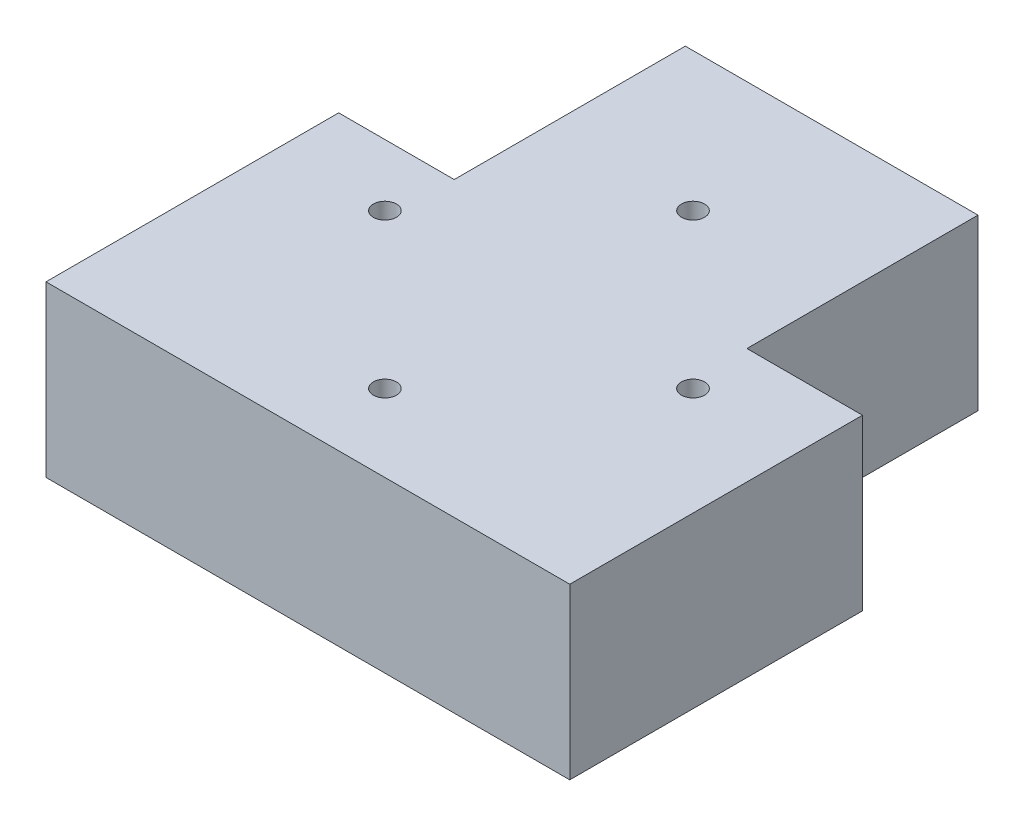
SolidWorks part; units mm, degrees
ref_plane "Alzado" through (0, 0, 0) normal (0, 0, 1) x (1, 0, 0)
ref_plane "Planta" through (0, 0, 0) normal (0, 1, 0) x (1, 0, 0)
ref_plane "Vista lateral" through (0, 0, 0) normal (1, 0, 0) x (0, 0, -1)
sketch "Croquis3" plane through (0, 0, 0) normal (0, 1, 0) x (1, 0, 0)
  circle A0 centre (0, 0) radius 11
  arc A1 (-42.801, 4.1321) -> (-38.4151, 2.54) centre (-35.0691, 18.5951) ccw
  arc A2 (-38.4151, 2.54) -> (-38.4968, 0.4081) centre (0, 0) ccw
  arc A3 (-38.4968, 0.4081) -> (-42.9917, -0.8436) centre (-36.3896, -15.856) ccw
  arc A4 (-42.9917, -0.8436) -> (-42.9302, -2.4499) centre (0, 0) ccw
  arc A5 (-42.9302, -2.4499) -> (-38.3526, -3.3538) centre (-37.4966, 13.0239) ccw
  arc A6 (-38.3526, -3.3538) -> (-38.108, -5.4732) centre (0, 0) ccw
  arc A7 (-38.108, -5.4732) -> (-42.3591, -7.3964) centre (-33.5427, -21.225) ccw
  arc A8 (-42.3591, -7.3964) -> (-42.0531, -8.9744) centre (0, 0) ccw
  arc A9 (-42.0531, -8.9744) -> (-37.3912, -9.169) centre (-39.0453, 7.1474) ccw
  arc A10 (-37.3912, -9.169) -> (-36.8259, -11.2263) centre (0, 0) ccw
  arc A11 (-36.8259, -11.2263) -> (-40.7336, -13.7758) centre (-29.9097, -26.0966) ccw
  arc A12 (-40.7336, -13.7758) -> (-40.1903, -15.2886) centre (0, 0) ccw
  arc A13 (-40.1903, -15.2886) -> (-35.5534, -14.7692) centre (-39.6787, 1.1034) ccw
  arc A14 (-35.5534, -14.7692) -> (-34.6806, -16.7161) centre (0, 0) ccw
  arc A15 (-34.6806, -16.7161) -> (-38.1534, -19.8323) centre (-25.5755, -30.3564) ccw
  arc A16 (-38.1534, -19.8323) -> (-37.3855, -21.2444) centre (0, 0) ccw
  arc A17 (-37.3855, -21.2444) -> (-32.8822, -20.0234) centre (-39.3821, -4.9664) ccw
  arc A18 (-32.8822, -20.0234) -> (-31.7225, -21.8142) centre (0, 0) ccw
  arc A19 (-31.7225, -21.8142) -> (-34.6789, -25.4239) centre (-20.6419, -33.9047) ccw
  arc A20 (-34.6789, -25.4239) -> (-33.7044, -26.7023) centre (0, 0) ccw
  arc A21 (-33.7044, -26.7023) -> (-29.4403, -24.8081) centre (-38.1625, -10.9199) ccw
  arc A22 (-29.4403, -24.8081) -> (-28.0208, -26.4009) centre (0, 0) ccw
  arc A23 (-28.0208, -26.4009) -> (-30.3915, -30.4197) centre (-15.2244, -36.6583) ccw
  arc A24 (-30.3915, -30.4197) -> (-29.2333, -31.5343) centre (0, 0) ccw
  arc A25 (-29.2333, -31.5343) -> (-25.3083, -29.0114) centre (-36.0483, -16.6174) ccw
  arc A26 (-25.3083, -29.0114) -> (-23.6623, -30.3689) centre (0, 0) ccw
  arc A27 (-23.6623, -30.3689) -> (-25.3918, -34.7024) centre (-9.4501, -38.5527) ccw
  arc A28 (-25.3918, -34.7024) -> (-24.077, -35.6272) centre (0, 0) ccw
  arc A29 (-24.077, -35.6272) -> (-20.5831, -32.5347) centre (-33.0892, -21.9254) ccw
  arc A30 (-20.5831, -32.5347) -> (-18.7492, -33.625) centre (0, 0) ccw
  arc A31 (-18.7492, -33.625) -> (-19.7969, -38.1718) centre (-3.4543, -39.5435) ccw
  arc A32 (-19.7969, -38.1718) -> (-18.3564, -38.885) centre (0, 0) ccw
  arc A33 (-18.3564, -38.885) -> (-15.3755, -35.2954) centre (-29.3545, -26.7195) ccw
  arc A34 (-15.3755, -35.2954) -> (-13.3966, -36.093) centre (0, 0) ccw
  arc A35 (-13.3966, -36.093) -> (-13.738, -40.7464) centre (2.6224, -39.6073) ccw
  arc A36 (-13.738, -40.7464) -> (-12.2055, -41.2314) centre (0, 0) ccw
  arc A37 (-12.2055, -41.2314) -> (-9.8075, -37.2288) centre (-24.9318, -30.8873) ccw
  arc A38 (-9.8075, -37.2288) -> (-7.73, -37.715) centre (0, 0) ccw
  arc A39 (-7.73, -37.715) -> (-7.3571, -42.3659) centre (8.6377, -38.7428) ccw
  arc A40 (-7.3571, -42.3659) -> (-5.7685, -42.6113) centre (0, 0) ccw
  arc A41 (-5.7685, -42.6113) -> (-4.0096, -38.2896) centre (-19.9247, -34.3311) ccw
  arc A42 (-4.0096, -38.2896) -> (-1.8823, -38.453) centre (0, 0) ccw
  arc A43 (-1.8823, -38.453) -> (-0.8037, -42.9925) centre (14.4506, -36.9703) ccw
  arc A44 (-0.8037, -42.9925) -> (0.8037, -42.9925) centre (0, 0) ccw
  arc A45 (0.8037, -42.9925) -> (1.8823, -38.453) centre (-14.4506, -36.9703) ccw
  arc A46 (1.8823, -38.453) -> (4.0096, -38.2896) centre (0, 0) ccw
  arc A47 (4.0096, -38.2896) -> (5.7685, -42.6113) centre (19.9247, -34.3311) ccw
  arc A48 (5.7685, -42.6113) -> (7.3571, -42.3659) centre (0, 0) ccw
  arc A49 (7.3571, -42.3659) -> (7.73, -37.715) centre (-8.6377, -38.7428) ccw
  arc A50 (7.73, -37.715) -> (9.8075, -37.2288) centre (0, 0) ccw
  arc A51 (9.8075, -37.2288) -> (12.2055, -41.2314) centre (24.9318, -30.8873) ccw
  arc A52 (12.2055, -41.2314) -> (13.738, -40.7464) centre (0, 0) ccw
  arc A53 (13.738, -40.7464) -> (13.3966, -36.093) centre (-2.6224, -39.6073) ccw
  arc A54 (13.3966, -36.093) -> (15.3755, -35.2954) centre (0, 0) ccw
  arc A55 (15.3755, -35.2954) -> (18.3564, -38.885) centre (29.3545, -26.7195) ccw
  arc A56 (18.3564, -38.885) -> (19.7969, -38.1718) centre (0, 0) ccw
  arc A57 (19.7969, -38.1718) -> (18.7492, -33.625) centre (3.4543, -39.5435) ccw
  arc A58 (18.7492, -33.625) -> (20.5831, -32.5347) centre (0, 0) ccw
  arc A59 (20.5831, -32.5347) -> (24.077, -35.6272) centre (33.0892, -21.9254) ccw
  arc A60 (24.077, -35.6272) -> (25.3918, -34.7024) centre (0, 0) ccw
  arc A61 (25.3918, -34.7024) -> (23.6623, -30.3689) centre (9.4501, -38.5527) ccw
  arc A62 (23.6623, -30.3689) -> (25.3083, -29.0114) centre (0, 0) ccw
  arc A63 (25.3083, -29.0114) -> (29.2333, -31.5343) centre (36.0483, -16.6174) ccw
  arc A64 (29.2333, -31.5343) -> (30.3915, -30.4197) centre (0, 0) ccw
  arc A65 (30.3915, -30.4197) -> (28.0208, -26.4009) centre (15.2244, -36.6583) ccw
  arc A66 (28.0208, -26.4009) -> (29.4403, -24.8081) centre (0, 0) ccw
  arc A67 (29.4403, -24.8081) -> (33.7044, -26.7023) centre (38.1625, -10.9199) ccw
  arc A68 (33.7044, -26.7023) -> (34.6789, -25.4239) centre (0, 0) ccw
  arc A69 (34.6789, -25.4239) -> (31.7225, -21.8142) centre (20.6419, -33.9047) ccw
  arc A70 (31.7225, -21.8142) -> (32.8822, -20.0234) centre (0, 0) ccw
  arc A71 (32.8822, -20.0234) -> (37.3855, -21.2444) centre (39.3821, -4.9664) ccw
  arc A72 (37.3855, -21.2444) -> (38.1534, -19.8323) centre (0, 0) ccw
  arc A73 (38.1534, -19.8323) -> (34.6806, -16.7161) centre (25.5755, -30.3564) ccw
  arc A74 (34.6806, -16.7161) -> (35.5534, -14.7692) centre (0, 0) ccw
  arc A75 (35.5534, -14.7692) -> (40.1903, -15.2886) centre (39.6787, 1.1034) ccw
  arc A76 (40.1903, -15.2886) -> (40.7336, -13.7758) centre (0, 0) ccw
  arc A77 (40.7336, -13.7758) -> (36.8259, -11.2263) centre (29.9097, -26.0966) ccw
  arc A78 (36.8259, -11.2263) -> (37.3912, -9.169) centre (0, 0) ccw
  arc A79 (37.3912, -9.169) -> (42.0531, -8.9744) centre (39.0453, 7.1474) ccw
  arc A80 (42.0531, -8.9744) -> (42.3591, -7.3964) centre (0, 0) ccw
  arc A81 (42.3591, -7.3964) -> (38.108, -5.4732) centre (33.5427, -21.225) ccw
  arc A82 (38.108, -5.4732) -> (38.3526, -3.3538) centre (0, 0) ccw
  arc A83 (38.3526, -3.3538) -> (42.9302, -2.4499) centre (37.4966, 13.0239) ccw
  arc A84 (42.9302, -2.4499) -> (42.9917, -0.8436) centre (0, 0) ccw
  arc A85 (42.9917, -0.8436) -> (38.4968, 0.4081) centre (36.3896, -15.856) ccw
  arc A86 (38.4968, 0.4081) -> (38.4151, 2.54) centre (0, 0) ccw
  arc A87 (38.4151, 2.54) -> (42.801, 4.1321) centre (35.0691, 18.5951) ccw
  arc A88 (42.801, 4.1321) -> (42.6167, 5.7289) centre (0, 0) ccw
  arc A89 (42.6167, 5.7289) -> (37.9834, 6.2798) centre (38.3836, -10.1153) ccw
  arc A90 (37.9834, 6.2798) -> (37.5772, 8.3743) centre (0, 0) ccw
  arc A91 (37.5772, 8.3743) -> (41.6686, 10.6172) centre (31.8196, 23.7304) ccw
  arc A92 (41.6686, 10.6172) -> (41.2427, 12.1672) centre (0, 0) ccw
  arc A93 (41.2427, 12.1672) -> (36.5796, 12.0043) centre (39.4778, -4.1376) ccw
  arc A94 (36.5796, 12.0043) -> (35.8584, 14.0123) centre (0, 0) ccw
  arc A95 (35.8584, 14.0123) -> (39.5596, 16.8535) centre (27.8242, 28.3095) ccw
  arc A96 (39.5596, 16.8535) -> (38.902, 18.3203) centre (0, 0) ccw
  arc A97 (38.902, 18.3203) -> (34.3185, 17.4475) centre (39.6468, 1.9372) ccw
  arc A98 (34.3185, 17.4475) -> (33.2992, 19.3219) centre (0, 0) ccw
  arc A99 (33.2992, 19.3219) -> (36.5233, 22.6947) centre (23.1767, 32.2251) ccw
  arc A100 (36.5233, 22.6947) -> (35.6495, 24.0439) centre (0, 0) ccw
  arc A101 (35.6495, 24.0439) -> (31.2529, 22.4817) centre (38.8864, 7.9665) ccw
  arc A102 (31.2529, 22.4817) -> (29.9595, 24.1785) centre (0, 0) ccw
  arc A103 (29.9595, 24.1785) -> (32.6309, 28.004) centre (17.9859, 35.3854) ccw
  arc A104 (32.6309, 28.004) -> (31.5614, 29.204) centre (0, 0) ccw
  arc A105 (31.5614, 29.204) -> (27.4548, 26.989) centre (37.2146, 13.8092) ccw
  arc A106 (27.4548, 26.989) -> (25.9176, 28.4685) centre (0, 0) ccw
  arc A107 (25.9176, 28.4685) -> (27.9737, 32.6569) centre (12.3736, 37.7162) ccw
  arc A108 (27.9737, 32.6569) -> (26.7336, 33.6796) centre (0, 0) ccw
  arc A109 (26.7336, 33.6796) -> (23.0132, 30.8636) centre (34.6705, 19.3281) ccw
  arc A110 (23.0132, 30.8636) -> (21.2681, 32.0911) centre (0, 0) ccw
  arc A111 (21.2681, 32.0911) -> (22.6608, 36.5443) centre (6.4712, 39.163) ccw
  arc A112 (22.6608, 36.5443) -> (21.2791, 37.3658) centre (0, 0) ccw
  arc A113 (21.2791, 37.3658) -> (18.0322, 34.0149) centre (31.3137, 24.394) ccw
  arc A114 (18.0322, 34.0149) -> (16.1202, 34.9616) centre (0, 0) ccw
  arc A115 (16.1202, 34.9616) -> (16.8168, 39.5752) centre (0.4172, 39.6919) ccw
  arc A116 (16.8168, 39.5752) -> (15.3259, 40.1761) centre (0, 0) ccw
  arc A117 (15.3259, 40.1761) -> (12.6285, 36.3688) centre (27.223, 28.8881) ccw
  arc A118 (12.6285, 36.3688) -> (10.5944, 37.0126) centre (0, 0) ccw
  arc A119 (10.5944, 37.0126) -> (10.5786, 41.6785) centre (-5.6466, 39.2904) ccw
  arc A120 (10.5786, 41.6785) -> (9.0134, 42.0447) centre (0, 0) ccw
  arc A121 (9.0134, 42.0447) -> (6.9289, 37.8704) centre (22.4942, 32.7052) ccw
  arc A122 (6.9289, 37.8704) -> (4.8203, 38.196) centre (0, 0) ccw
  arc A123 (4.8203, 38.196) -> (4.0924, 42.8048) centre (-11.5781, 37.968) ccw
  arc A124 (4.0924, 42.8048) -> (2.4897, 42.9279) centre (0, 0) ccw
  arc A125 (2.4897, 42.9279) -> (1.0668, 38.4842) centre (17.2382, 35.7556) ccw
  arc A126 (1.0668, 38.4842) -> (-1.0668, 38.4842) centre (0, 0) ccw
  arc A127 (-1.0668, 38.4842) -> (-2.4897, 42.9279) centre (-17.2382, 35.7556) ccw
  arc A128 (-2.4897, 42.9279) -> (-4.0924, 42.8048) centre (0, 0) ccw
  arc A129 (-4.0924, 42.8048) -> (-4.8203, 38.196) centre (11.5781, 37.968) ccw
  arc A130 (-4.8203, 38.196) -> (-6.9289, 37.8704) centre (0, 0) ccw
  arc A131 (-6.9289, 37.8704) -> (-9.0134, 42.0447) centre (-22.4942, 32.7052) ccw
  arc A132 (-9.0134, 42.0447) -> (-10.5786, 41.6785) centre (0, 0) ccw
  arc A133 (-10.5786, 41.6785) -> (-10.5944, 37.0126) centre (5.6466, 39.2904) ccw
  arc A134 (-10.5944, 37.0126) -> (-12.6285, 36.3688) centre (0, 0) ccw
  arc A135 (-12.6285, 36.3688) -> (-15.3259, 40.1761) centre (-27.223, 28.8881) ccw
  arc A136 (-15.3259, 40.1761) -> (-16.8168, 39.5752) centre (0, 0) ccw
  arc A137 (-16.8168, 39.5752) -> (-16.1202, 34.9616) centre (-0.4172, 39.6919) ccw
  arc A138 (-16.1202, 34.9616) -> (-18.0322, 34.0149) centre (0, 0) ccw
  arc A139 (-18.0322, 34.0149) -> (-21.2791, 37.3658) centre (-31.3137, 24.394) ccw
  arc A140 (-21.2791, 37.3658) -> (-22.6608, 36.5443) centre (0, 0) ccw
  arc A141 (-22.6608, 36.5443) -> (-21.2681, 32.0911) centre (-6.4712, 39.163) ccw
  arc A142 (-21.2681, 32.0911) -> (-23.0132, 30.8636) centre (0, 0) ccw
  arc A143 (-23.0132, 30.8636) -> (-26.7336, 33.6796) centre (-34.6705, 19.3281) ccw
  arc A144 (-26.7336, 33.6796) -> (-27.9737, 32.6569) centre (0, 0) ccw
  arc A145 (-27.9737, 32.6569) -> (-25.9176, 28.4685) centre (-12.3736, 37.7162) ccw
  arc A146 (-25.9176, 28.4685) -> (-27.4548, 26.989) centre (0, 0) ccw
  arc A147 (-27.4548, 26.989) -> (-31.5614, 29.204) centre (-37.2146, 13.8092) ccw
  arc A148 (-31.5614, 29.204) -> (-32.6309, 28.004) centre (0, 0) ccw
  arc A149 (-32.6309, 28.004) -> (-29.9595, 24.1785) centre (-17.9859, 35.3854) ccw
  arc A150 (-29.9595, 24.1785) -> (-31.2529, 22.4817) centre (0, 0) ccw
  arc A151 (-31.2529, 22.4817) -> (-35.6495, 24.0439) centre (-38.8864, 7.9665) ccw
  arc A152 (-35.6495, 24.0439) -> (-36.5233, 22.6947) centre (0, 0) ccw
  arc A153 (-36.5233, 22.6947) -> (-33.2992, 19.3219) centre (-23.1767, 32.2251) ccw
  arc A154 (-33.2992, 19.3219) -> (-34.3185, 17.4475) centre (0, 0) ccw
  arc A155 (-34.3185, 17.4475) -> (-38.902, 18.3203) centre (-39.6468, 1.9372) ccw
  arc A156 (-38.902, 18.3203) -> (-39.5596, 16.8535) centre (0, 0) ccw
  arc A157 (-39.5596, 16.8535) -> (-35.8584, 14.0123) centre (-27.8242, 28.3095) ccw
  arc A158 (-35.8584, 14.0123) -> (-36.5796, 12.0043) centre (0, 0) ccw
  arc A159 (-36.5796, 12.0043) -> (-41.2427, 12.1672) centre (-39.4778, -4.1376) ccw
  arc A160 (-41.2427, 12.1672) -> (-41.6686, 10.6172) centre (0, 0) ccw
  arc A161 (-41.6686, 10.6172) -> (-37.5772, 8.3743) centre (-31.8196, 23.7304) ccw
  arc A162 (-37.5772, 8.3743) -> (-37.9834, 6.2798) centre (0, 0) ccw
  arc A163 (-37.9834, 6.2798) -> (-42.6167, 5.7289) centre (-38.3836, -10.1153) ccw
  arc A164 (-42.6167, 5.7289) -> (-42.801, 4.1321) centre (0, 0) ccw
extrude "Saliente-Extruir1" add sketch "Croquis3" along normal blind 6
sketch "Croquis4" plane through (0, 6, 0) normal (0, 1, 0) x (1, 0, 0)
  line L0 (0, 0) -> (30, 0) construction
  line L1 (0, 0) -> (0, 30) construction
  line L2 (0, 28.45) -> (0, 31.55)
  line L3 (0, -28.45) -> (0, -31.55)
  arc A0 (0, -30) -> (0, 30) centre (0, 0) ccw construction
  arc A1 (0, -31.55) -> (0, 31.55) centre (0, 0) ccw
  arc A2 (0, -28.45) -> (0, 28.45) centre (0, 0) ccw
  point P4 (30, 0)
  dimension "D1" = 30
  dimension "D2" = 90
  dimension "D3" = 1.55
  dimension "D4" = 1.55
sketch "Croquis5" plane through (0, 6, 0) normal (0, 1, 0) x (1, 0, 0)
  line L0 (0, 0) -> (0, 20) construction
  circle A0 centre (0, 20) radius 1.7
  circle A1 centre (20, 0) radius 1.7
  circle A2 centre (0, -20) radius 1.7
  circle A3 centre (-20, 0) radius 1.7
  point P13 (0, 0)
  dimension "D1" = 3.4
  dimension "D2" = 20
  dimension "D3" = 4
extrude "Cortar-Extruir2" cut sketch "Croquis5" against normal through all
sketch "Croquis6" plane through (0, 6, 0) normal (0, 1, 0) x (1, 0, 0)
  circle A0 centre (0, 0) radius 11
  circle A1 centre (0, 0) radius 10.875
extrude "Saliente-Extruir2" add sketch "Croquis6" against normal up to surface (6 mm away) up to face at (0, 0, -18.3)
sketch "Croquis7" plane through (0, 6, 0) normal (0, 1, 0) x (1, 0, 0)
  circle A0 centre (0, 0) radius 10.875
extrude "Saliente-Extruir3" add sketch "Croquis7" against normal blind 6
sketch "Croquis8" plane through (0, 6, 0) normal (0, 1, 0) x (1, 0, 0)
  line L1 (-34, -30) -> (34, -30)
  line L2 (-34, -30) -> (-34, -26)
  line L3 (-34, -26) -> (34, -26)
  line L4 (34, -30) -> (34, -26)
  dimension "D1" = 26
  dimension "D2" = 4
  dimension "D3" = 34
  dimension "D4" = 34
extrude "Saliente-Extruir5" add sketch "Croquis8" against normal blind 6
sketch "Croquis9" plane through (0, 6, 0) normal (0, 1, 0) x (1, 0, 0)
  line L1 (-34, -30) -> (54.0336, -30)
  line L2 (-34, -30) -> (-34, -48.4767)
  line L3 (-34, -48.4767) -> (54.0336, -48.4767)
  line L4 (54.0336, -30) -> (54.0336, -48.4767)
extrude "Cortar-Extruir3" cut sketch "Croquis9" against normal blind 6
sketch "Croquis10" plane through (0, 6, 0) normal (0, 1, 0) x (1, 0, 0)
  line L1 (-34, -30) -> (-55.5503, -30)
  line L2 (-34, -30) -> (-34, 34)
  line L3 (-34, 34) -> (-55.5503, 34)
  line L4 (-55.5503, -30) -> (-55.5503, 34)
extrude "Cortar-Extruir4" cut sketch "Croquis10" against normal blind 6
sketch "Croquis11" plane through (0, 6, 0) normal (0, 1, 0) x (1, 0, 0)
  line L1 (34, -30) -> (53.0856, -30)
  line L2 (34, -30) -> (34, 34)
  line L3 (34, 34) -> (53.0856, 34)
  line L4 (53.0856, -30) -> (53.0856, 34)
extrude "Cortar-Extruir5" cut sketch "Croquis11" against normal blind 6
sketch "Croquis12" plane through (0, 6, 0) normal (0, 1, 0) x (1, 0, 0)
  line L0 (-34, -30) -> (34, -30) construction
  line L1 (-49.1042, 38) -> (54.6023, 38)
  line L2 (-49.1042, 38) -> (-49.1042, 63.5948)
  line L3 (-49.1042, 63.5948) -> (54.6023, 63.5948)
  line L4 (54.6023, 38) -> (54.6023, 63.5948)
  dimension "D1" = 68
extrude "Cortar-Extruir6" cut sketch "Croquis12" against normal blind 6
sketch "Croquis13" plane through (0, 6, 0) normal (0, 1, 0) x (1, 0, 0)
  line L0 (-34, 14.4677) -> (-34, 42.5272)
  line L1 (-34, -20.4581) -> (-34, 18.0603) construction
  line L2 (-4.3606, 38) -> (-34, 38)
  line L3 (-6.1784, 38) -> (6.1784, 38) construction
  line L4 (-34, 14.4677) -> (-4.3606, 38)
extrude "Saliente-Extruir7" add sketch "Croquis13" against normal blind 6 contours L0 L4 L2
sketch "Croquis14" plane through (0, 6, 0) normal (0, 1, 0) x (1, 0, 0)
  line L0 (-34, -8.678) -> (-34, -30)
  line L1 (-34, -20.4581) -> (-34, 38) construction
  line L2 (-34, -30) -> (-13.0531, -30)
  line L3 (-34, -30) -> (34, -30) construction
  line L4 (-13.0531, -30) -> (-34, -8.678)
  line L5 (16.5039, -30) -> (34, -30)
  line L6 (34, -30) -> (34, -14.8294)
  line L7 (34, 18.0603) -> (34, -20.4581) construction
  line L8 (34, -14.8294) -> (16.5039, -30)
  line L9 (34, 14.1274) -> (34, 42.034)
  line L10 (-2.8519, 38) -> (34, 38)
  line L11 (-34, 38) -> (6.1784, 38) construction
  line L12 (-2.8519, 38) -> (34, 14.1274)
  arc M1 (6.9289, 37.8704) -> (6.1784, 38) centre (0, 0) ccw
  arc M4 (-34, -20.4581) -> (-32.8822, -20.0234) centre (-39.3821, -4.9664) ccw
  arc M5 (-32.8822, -20.0234) -> (-31.7225, -21.8142) centre (0, 0) ccw
  arc M6 (-31.7225, -21.8142) -> (-34, -24.3905) centre (-20.6419, -33.9047) ccw
  arc M10 (34, -24.3905) -> (31.7225, -21.8142) centre (20.6419, -33.9047) ccw
  arc M11 (31.7225, -21.8142) -> (32.8822, -20.0234) centre (0, 0) ccw
  arc M12 (32.8822, -20.0234) -> (34, -20.4581) centre (39.3821, -4.9664) ccw
  arc M14 (34, 18.0603) -> (33.2992, 19.3219) centre (0, 0) ccw
  arc M15 (33.2992, 19.3219) -> (34, 19.9038) centre (23.1767, 32.2251) ccw
  arc M17 (34, 23.6217) -> (31.2529, 22.4817) centre (38.8864, 7.9665) ccw
  arc M18 (31.2529, 22.4817) -> (29.9595, 24.1785) centre (0, 0) ccw
  arc M19 (29.9595, 24.1785) -> (32.6309, 28.004) centre (17.9859, 35.3854) ccw
  arc M20 (32.6309, 28.004) -> (31.5614, 29.204) centre (0, 0) ccw
  arc M21 (31.5614, 29.204) -> (27.4548, 26.989) centre (37.2146, 13.8092) ccw
  arc M22 (27.4548, 26.989) -> (25.9176, 28.4685) centre (0, 0) ccw
  arc M23 (25.9176, 28.4685) -> (27.9737, 32.6569) centre (12.3736, 37.7162) ccw
  arc M24 (27.9737, 32.6569) -> (26.7336, 33.6796) centre (0, 0) ccw
  arc M25 (26.7336, 33.6796) -> (23.0132, 30.8636) centre (34.6705, 19.3281) ccw
  arc M26 (23.0132, 30.8636) -> (21.2681, 32.0911) centre (0, 0) ccw
  arc M27 (21.2681, 32.0911) -> (22.6608, 36.5443) centre (6.4712, 39.163) ccw
  arc M28 (22.6608, 36.5443) -> (21.2791, 37.3658) centre (0, 0) ccw
  arc M29 (21.2791, 37.3658) -> (18.0322, 34.0149) centre (31.3137, 24.394) ccw
  arc M30 (18.0322, 34.0149) -> (16.1202, 34.9616) centre (0, 0) ccw
  arc M31 (16.1202, 34.9616) -> (16.7297, 38) centre (0.4172, 39.6919) ccw
  arc M33 (13.5873, 38) -> (12.6285, 36.3688) centre (27.223, 28.8881) ccw
  arc M34 (12.6285, 36.3688) -> (10.5944, 37.0126) centre (0, 0) ccw
  arc M35 (10.5944, 37.0126) -> (10.7025, 38) centre (-5.6466, 39.2904) ccw
  arc M37 (6.9725, 38) -> (6.9289, 37.8704) centre (22.4942, 32.7052) ccw
  arc M38 (29.4403, -24.8081) -> (31.7165, -26) centre (38.1625, -10.9199) ccw
  line M39 (31.7165, -26) -> (28.3932, -26)
  arc M40 (28.3932, -26) -> (29.4403, -24.8081) centre (0, 0) ccw
  arc M41 (-29.4403, -24.8081) -> (-28.3932, -26) centre (0, 0) ccw
  line M42 (-28.3932, -26) -> (-31.7165, -26)
  arc M43 (-31.7165, -26) -> (-29.4403, -24.8081) centre (-38.1625, -10.9199) ccw
extrude "Saliente-Extruir8" add sketch "Croquis14" against normal blind 6 contours M41 M43 M42 | L0 M4 M6 M5 | L6 M10 M12 M11 | M38 M40 M39 | L10 L9 M31 M30 M29 M28 M27 M26 M25 M24 M23 M22 M21 M20 M19 M18 M17 | L10 M1 M37 | L10 M35 M34 M33 | L9 M14 M15
sketch "Croquis15" plane through (-34, 0, 0) normal (-1, 0, 0) x (0, 0, 1)
  line L1 (-38, 0) -> (30, 0)
  line L2 (-38, 0) -> (-38, 3)
  line L3 (-38, 3) -> (30, 3)
  line L4 (30, 0) -> (30, 3)
extrude "Cortar-Extruir7" cut sketch "Croquis15" against normal blind 90
sketch "Croquis16" plane through (0, 3, 0) normal (0, -1, 0) x (-1, 0, 0)
  line L0 (30, -26) -> (30, 4)
  line L1 (30, 4) -> (15, 4)
  line L2 (15, 4) -> (15, 34)
  line L3 (15, 34) -> (-15, 34)
  line L4 (-15, 34) -> (-15, 4)
  line L5 (-15, 4) -> (-30, 4)
  line L6 (-30, 4) -> (-30, -26)
  line L7 (-30, -26) -> (30, -26)
  line L8 (34, -30) -> (34, 38) construction
  line L9 (-34, -30) -> (34, -30) construction
  line L10 (34, -30) -> (34, 8)
  line L11 (34, 8) -> (19, 8)
  line L12 (19, 8) -> (19, 38)
  line L13 (-34, 38) -> (34, 38) construction
  line L14 (19, 38) -> (-19, 38)
  line L15 (-19, 38) -> (-19, 8)
  line L16 (-19, 8) -> (-34, 8)
  line L17 (-34, 38) -> (-34, -30) construction
  line L18 (-34, 8) -> (-34, -30)
  line L19 (-34, -30) -> (34, -30)
  dimension "D1" = 4
  dimension "D2" = 4
extrude "Saliente-Extruir9" add sketch "Croquis16" along normal blind 15
sketch "Croquis17" plane through (0, 3, 0) normal (0, -1, 0) x (-1, 0, 0)
  line L1 (19, 38) -> (34, 38)
  line L2 (19, 38) -> (19, 8)
  line L3 (19, 8) -> (34, 8)
  line L4 (34, 38) -> (34, 8)
extrude "Cortar-Extruir8" cut sketch "Croquis17" against normal blind 15
sketch "Croquis18" plane through (0, 3, 0) normal (0, -1, 0) x (-1, 0, 0)
  line L1 (-19, 8) -> (-42.2207, 8)
  line L2 (-19, 8) -> (-19, 41.839)
  line L3 (-19, 41.839) -> (-42.2207, 41.839)
  line L4 (-42.2207, 8) -> (-42.2207, 41.839)
extrude "Cortar-Extruir10" cut sketch "Croquis18" against normal blind 15
sketch "Croquis19" plane through (0, 6, 0) normal (0, 1, 0) x (1, 0, 0)
  line L0 (-34, -30) -> (-34, 8)
  line L1 (-34, 8) -> (-19, 8)
  line L2 (-19, 8) -> (-19, 38)
  line L3 (-19, 38) -> (19, 38)
  line L4 (19, 38) -> (19, 8)
  line L5 (19, 8) -> (34, 8)
  line L6 (34, 8) -> (34, -30)
  line L7 (34, -30) -> (-34, -30)
  circle A0 centre (-20, 0) radius 1.5
  circle A1 centre (0, -20) radius 1.5
  circle A2 centre (20, 0) radius 1.5
  circle A3 centre (0, 20) radius 1.5
extrude "Saliente-Extruir10" add sketch "Croquis19" along normal blind 4
sketch "Croquis20" plane through (0, 3, 0) normal (0, -1, 0) x (-1, 0, 0)
  circle A0 centre (0, -20) radius 2.75
  circle A1 centre (-20, 0) radius 2.75
  circle A2 centre (0, 20) radius 2.75
  circle A3 centre (20, 0) radius 2.75
extrude "Cortar-Extruir12" cut sketch "Croquis20" against normal blind 4
